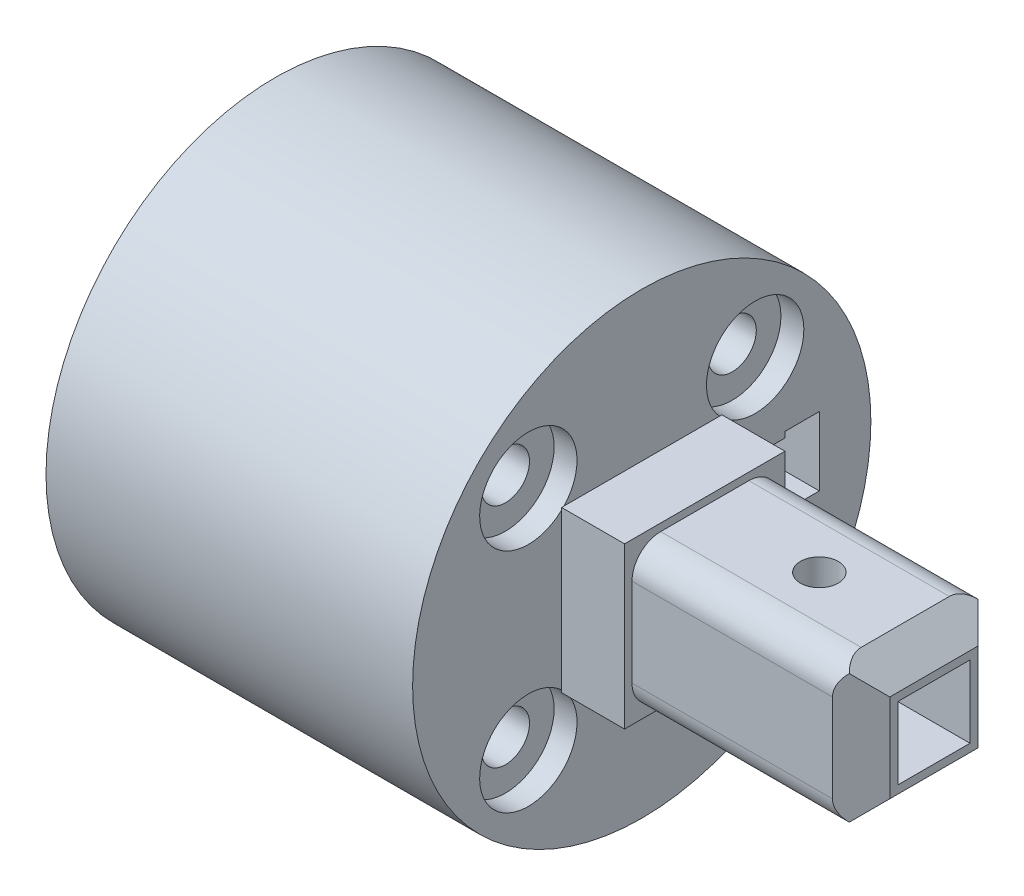
SolidWorks part; units mm, degrees
ref_plane "前视基准面" through (0, 0, 0) normal (0, 0, 1) x (1, 0, 0)
ref_plane "上视基准面" through (0, 0, 0) normal (0, 1, 0) x (1, 0, 0)
ref_plane "右视基准面" through (0, 0, 0) normal (1, 0, 0) x (0, 0, -1)
sketch "草图1" plane through (0, 0, 0) normal (1, 0, 0) x (0, 0, -1)
  circle A0 centre (0, 0) radius 20
  dimension "D1" = 40
extrude "凸台-拉伸1" add sketch "草图1" along normal blind 5
sketch "草图2" plane through (5, 0, 0) normal (1, 0, 0) x (0, 0, -1)
  line L1 (-3.15, -3.15) -> (3.15, -3.15)
  line L2 (-3.15, -3.15) -> (-3.15, 3.15)
  line L3 (-3.15, 3.15) -> (3.15, 3.15)
  line L4 (3.15, -3.15) -> (3.15, 3.15)
  line L5 (-3.15, -3.15) -> (3.15, 3.15) construction
  line L6 (-3.15, 3.15) -> (3.15, -3.15) construction
  point P0 (0, 0)
  dimension "D1" = 6.3
  dimension "D2" = 6.3
extrude "切除-拉伸1" cut sketch "草图2" against normal blind 5
sketch "草图4" plane through (0, 0, 0) normal (-1, 0, 0) x (0, 0, 1)
  circle A0 centre (0, 0) radius 20
  circle A1 centre (0, 0) radius 10
  dimension "D1" = 20
extrude "凸台-拉伸2" add sketch "草图4" along normal blind 7
sketch "草图3" plane through (0, 0, 0) normal (-1, 0, 0) x (0, 0, 1)
  line L0 (0, 0) -> (20, 0) construction
  line L1 (0, 0) -> (21.8171, -21.8171) construction
  circle A0 centre (0, 0) radius 14 construction
  circle A3 centre (9.8995, -9.8995) radius 2.1
  circle A4 centre (0, 0) radius 14 construction
  circle A5 centre (-9.8995, -9.8995) radius 2.1
  circle A6 centre (0, 0) radius 14 construction
  circle A7 centre (-9.8995, 9.8995) radius 2.1
  circle A8 centre (0, 0) radius 14 construction
  circle A9 centre (9.8995, 9.8995) radius 2.1
  point P22 (0, 0)
  dimension "D1" = 28
  dimension "D2" = 4.2
  dimension "D3" = 45
  dimension "D4" = 4
extrude "切除-拉伸2" cut sketch "草图3" against normal blind 20 and the other way blind 20
sketch "草图5" plane through (5, 0, 0) normal (1, 0, 0) x (0, 0, -1)
  line L1 (15.5, -3) -> (12.5, -3)
  line L2 (15.5, -3) -> (15.5, 3)
  line L3 (15.5, 3) -> (12.5, 3)
  line L4 (12.5, -3) -> (12.5, 3)
  line L5 (15.5, -3) -> (12.5, 3) construction
  line L6 (15.5, 3) -> (12.5, -3) construction
  point P0 (14, 0)
  dimension "D1" = 14
  dimension "D2" = 3
  dimension "D3" = 6
extrude "切除-拉伸3" cut sketch "草图5" against normal blind 13
chamfer "倒角1" distance 1 angle 45 4 edges at (-7, 3, -14) (-7, 0, -15.5) (-7, -3, -14) (-7, 0, -12.5)
sketch "草图6" plane through (-7, 0, 0) normal (-1, 0, 0) x (0, 0, 1)
  circle A0 centre (0, 0) radius 20
  circle A1 centre (0, 0) radius 18
  dimension "D1" = 40
  dimension "D2" = 36
extrude "凸台-拉伸3" add sketch "草图6" along normal blind 20
chamfer "倒角2" distance 1 angle 45 1 edges at (-27, 0, 18)
sketch "草图7" plane through (5, 0, 0) normal (1, 0, 0) x (0, 0, -1)
  circle A0 centre (-9.8995, 9.8995) radius 4.25
  circle A1 centre (9.8995, 9.8995) radius 4.25
  circle A2 centre (9.8995, -9.8995) radius 4.25
  circle A3 centre (-9.8995, -9.8995) radius 4.25
  point P12 (0, 0)
  dimension "D1" = 8.5
  dimension "D2" = 4
extrude "切除-拉伸4" cut sketch "草图7" against normal blind 2
sketch "草图8" plane through (5, 0, 0) normal (1, 0, 0) x (0, 0, -1)
  line L1 (7, -7) -> (-7, -7)
  line L2 (7, -7) -> (7, 7)
  line L3 (7, 7) -> (-7, 7)
  line L4 (-7, -7) -> (-7, 7)
  line L5 (7, -7) -> (-7, 7) construction
  line L6 (7, 7) -> (-7, -7) construction
  point P0 (0, 0)
  dimension "D1" = 14
  dimension "D2" = 14
extrude "凸台-拉伸4" add sketch "草图8" along normal blind 5.5
sketch "草图9" plane through (5, 0, 0) normal (-1, 0, 0) x (0, 0, 1)
  line L1 (-3.15, -3.15) -> (3.15, -3.15)
  line L2 (-3.15, -3.15) -> (-3.15, 3.15)
  line L3 (-3.15, 3.15) -> (3.15, 3.15)
  line L4 (3.15, -3.15) -> (3.15, 3.15)
  line L5 (-3.15, -3.15) -> (3.15, 3.15) construction
  line L6 (-3.15, 3.15) -> (3.15, -3.15) construction
  point P0 (0, 0)
  dimension "D1" = 6.3
extrude "切除-拉伸5" cut sketch "草图9" against normal blind 10
sketch "草图10" plane through (0, 0, -7) normal (0, 0, -1) x (-1, 0, 0)
  line L0 (-5, -6.7922) -> (-5, 6.7922) construction
  line L1 (-3.5, -2.5) -> (-6.5, -2.5)
  line L2 (-3.5, -2.5) -> (-3.5, 2.5)
  line L3 (-3.5, 2.5) -> (-6.5, 2.5)
  line L4 (-6.5, -2.5) -> (-6.5, 2.5)
  line L5 (-3.5, -2.5) -> (-6.5, 2.5) construction
  line L6 (-3.5, 2.5) -> (-6.5, -2.5) construction
  point P0 (-5, 0)
  dimension "D1" = 3
  dimension "D2" = 5
extrude "切除-拉伸6" cut sketch "草图10" against normal blind 5 and the other way blind 6
fillet "圆角1" radius 4 1 edges at (3.5, 0, -12.5)
fillet "圆角2" radius 2 1 edges at (6.5, 0, -3.15)
sketch "草图11" plane through (10.5, 0, 0) normal (1, 0, 0) x (0, 0, -1)
  line L1 (6.35, -6.35) -> (-6.35, -6.35)
  line L2 (6.35, -6.35) -> (6.35, 6.35)
  line L3 (6.35, 6.35) -> (-6.35, 6.35)
  line L4 (-6.35, -6.35) -> (-6.35, 6.35)
  line L5 (6.35, -6.35) -> (-6.35, 6.35) construction
  line L6 (6.35, 6.35) -> (-6.35, -6.35) construction
  line L8 (-3.15, -3.15) -> (3.15, -3.15)
  line L9 (-3.15, -3.15) -> (-3.15, 3.15)
  line L10 (-3.15, 3.15) -> (3.15, 3.15)
  line L11 (3.15, -3.15) -> (3.15, 3.15)
  line L12 (-3.15, -3.15) -> (3.15, 3.15) construction
  line L13 (-3.15, 3.15) -> (3.15, -3.15) construction
  point P0 (0, 0)
  point P6 (0, 0)
  dimension "D1" = 12.7
  dimension "D2" = 12.7
extrude "凸台-拉伸5" add sketch "草图11" along normal blind 20
chamfer "倒角3" distance 2.5 angle 45 4 edges at (30.5, 6.35, 0) (30.5, 0, -6.35) (30.5, -6.35, 0) (30.5, 0, 6.35)
sketch "草图12" plane through (0, -6.35, 0) normal (0, -1, 0) x (1, 0, 0)
  line L0 (10.5, 6.35) -> (10.5, -6.35) construction
  circle A0 centre (20.5, 0) radius 1.65
  dimension "D1" = 3.3
  dimension "D2" = 10
extrude "切除-拉伸7" cut sketch "草图12" against normal blind 20
fillet "圆角3" radius 2.5 4 edges at (19.25, -6.35, 6.35) (19.25, 6.35, 6.35) (19.25, 6.35, -6.35) (19.25, -6.35, -6.35)
